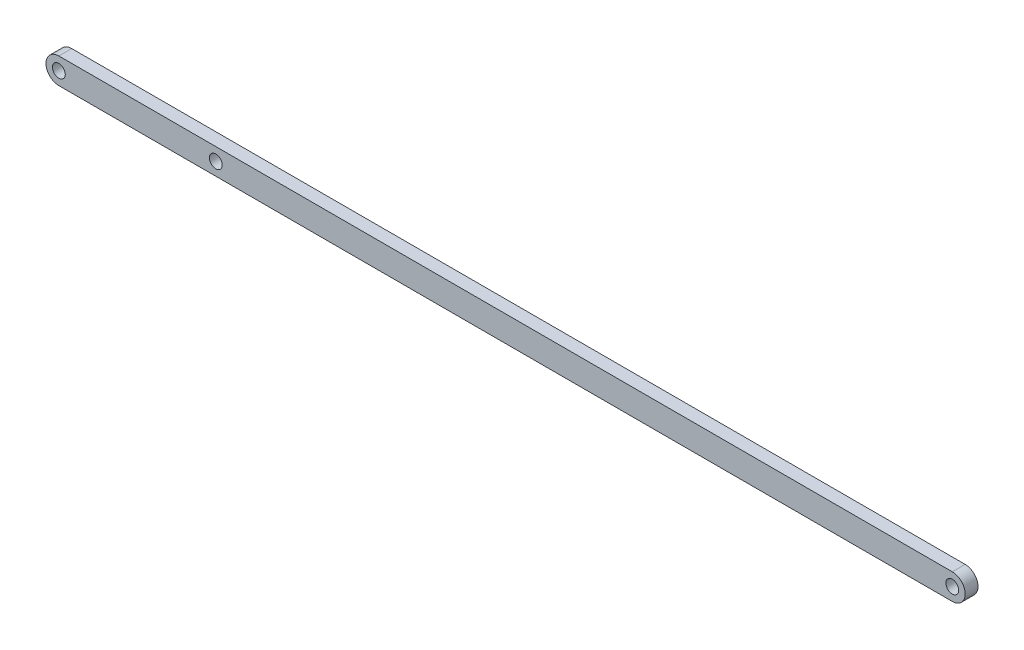
SolidWorks part; units mm, degrees
ref_plane "Plano frontal" through (0, 0, 0) normal (0, 0, 1) x (1, 0, 0)
ref_plane "Plano superior" through (0, 0, 0) normal (0, 1, 0) x (1, 0, 0)
ref_plane "Plano direito" through (0, 0, 0) normal (1, 0, 0) x (0, 0, -1)
sketch "Esboço1" plane through (0, 0, 0) normal (0, 0, 1) x (1, 0, 0)
  line L0 (173.74, 5) -> (-173.74, 5)
  line L1 (-14.1836, 0) -> (14.1836, 0) construction
  line L2 (173.74, -5) -> (-173.74, -5)
  arc A0 (-173.74, 5) -> (-173.74, -5) centre (-173.74, 0) ccw
  arc A1 (173.74, 5) -> (173.74, -5) centre (173.74, 0) cw
  circle A2 centre (-173.74, 0) radius 2.5
  circle A3 centre (173.74, 0) radius 2.5
  circle A4 centre (-112.7, 0) radius 2.5
  point P3 (0, 5)
  dimension "D3" = 61.04
  dimension "D1" = 5
  dimension "D2" = 347.48
extrude "Ressalto-extrusão1" add sketch "Esboço1" along normal blind 5
